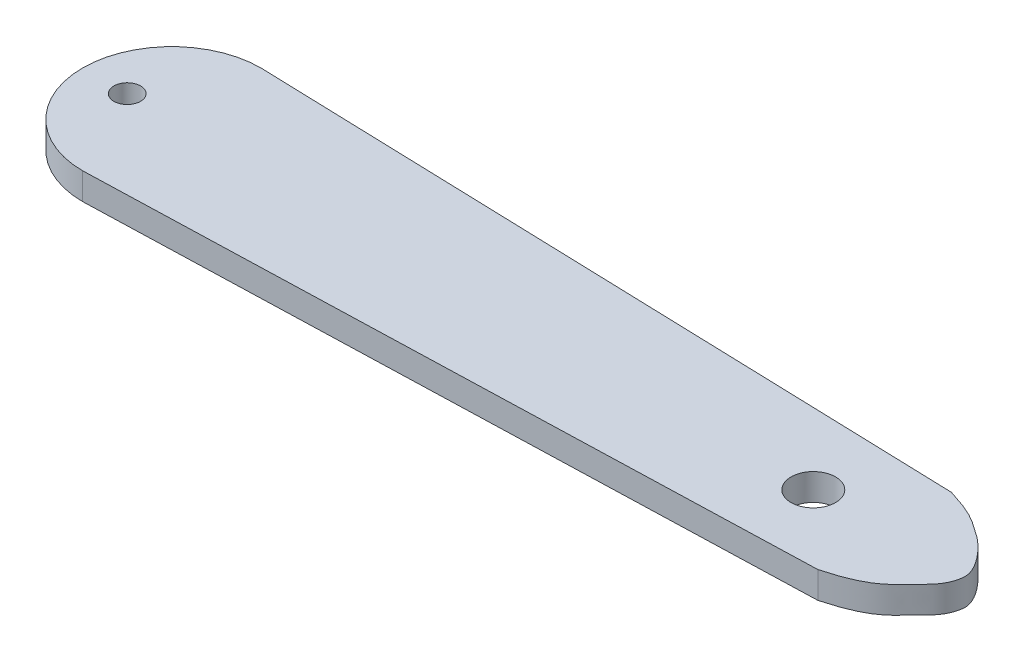
SolidWorks part; units mm, degrees
ref_plane "Piano frontale" through (0, 0, 0) normal (0, 0, 1) x (1, 0, 0)
ref_plane "Piano superiore" through (0, 0, 0) normal (0, 1, 0) x (1, 0, 0)
ref_plane "Piano destro" through (0, 0, 0) normal (1, 0, 0) x (0, 0, -1)
sketch "Schizzo1" plane through (0, 0, 0) normal (0, 1, 0) x (1, 0, 0)
  line L0 (-50, 10) -> (30, 7.5)
  line L1 (-50, -10) -> (30, -7.5)
  arc A0 (-50, -10) -> (-50, 10) centre (-50, 0) cw
  spline S1 degree 3 poles (30, 7.5) (33.2617, 6.4815) (33.8445, 5.8884) (36.6622, 4.0133) (39.1609, 1.1862) (38.6753, -1.9756) (37.3902, -2.9246) (35.3477, -5.1088) (33.4325, -6.5906) (30, -7.5) knots 0 0 0 0 0.303836 0.360141 0.54051 0.596736 0.866179 0.909873 1 1 1 1
  dimension "D1" = 80
  dimension "D2" = 10
  dimension "D5" = 50
  dimension "D3" = 15
  dimension "D4" = 7.5
extrude "Estrusione-Estrusione1" add sketch "Schizzo1" along normal blind 3
sketch "Schizzo2" plane through (0, 3, 0) normal (0, 1, 0) x (1, 0, 0)
  circle A0 centre (22, 0) radius 2.5
  circle A1 centre (-55, 0) radius 1.5
  dimension "D1" = 5
  dimension "D2" = 3
  dimension "D3" = 22
  dimension "D4" = 55
extrude "Taglio-Estrusione1" cut sketch "Schizzo2" against normal blind 4
